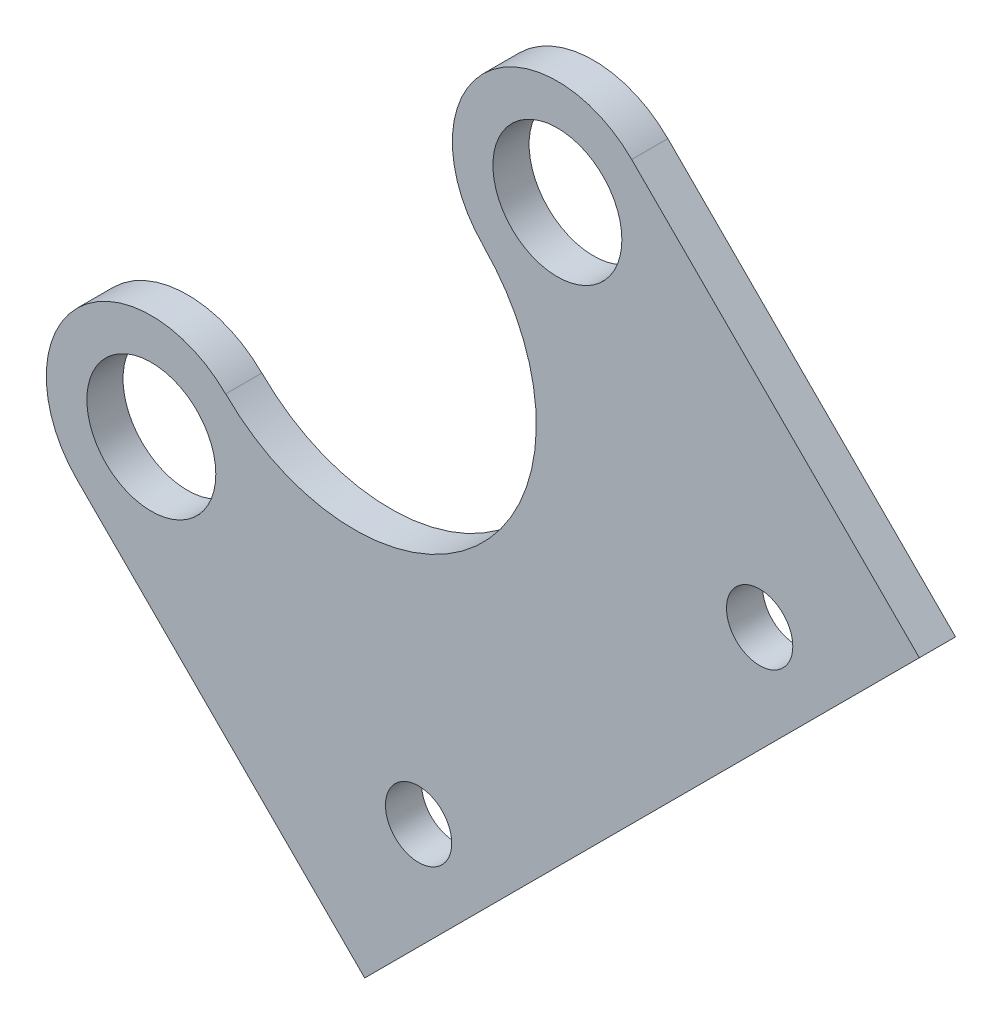
SolidWorks part; units mm, degrees
ref_plane "Front Plane" through (0, 0, 0) normal (0, 0, 1) x (1, 0, 0)
ref_plane "Top Plane" through (0, 0, 0) normal (0, 1, 0) x (1, 0, 0)
ref_plane "Right Plane" through (0, 0, 0) normal (1, 0, 0) x (0, 0, -1)
sketch "Sketch8" plane through (0, 0, 0) normal (0, 0, 1) x (1, 0, 0)
  line L0 (-22.9984, -22.9984) -> (0.859, -46.8559)
  line L1 (0.859, -46.8559) -> (46.8559, -0.859)
  line L2 (46.8559, -0.859) -> (22.9984, 22.9984)
  line L3 (10.6775, 10.6775) -> (10.6685, 10.6685)
  line L4 (-10.6685, -10.6685) -> (-10.6775, -10.6775)
  arc A0 (22.9984, 22.9984) -> (10.6775, 10.6775) centre (16.838, 16.838) ccw
  arc A1 (-10.6685, -10.6685) -> (10.6685, 10.6685) centre (0, 0) ccw
  arc A2 (-10.6775, -10.6775) -> (-22.9984, -22.9984) centre (-16.838, -16.838) ccw
  circle A3 centre (33.6102, -5.291) radius 2.75
  circle A4 centre (16.838, 16.838) radius 5.3467
  circle A5 centre (-16.838, -16.838) radius 5.3467
  circle A6 centre (5.3259, -33.5753) radius 2.75
extrude "Boss-Extrude1" add sketch "Sketch8" along normal blind 3
